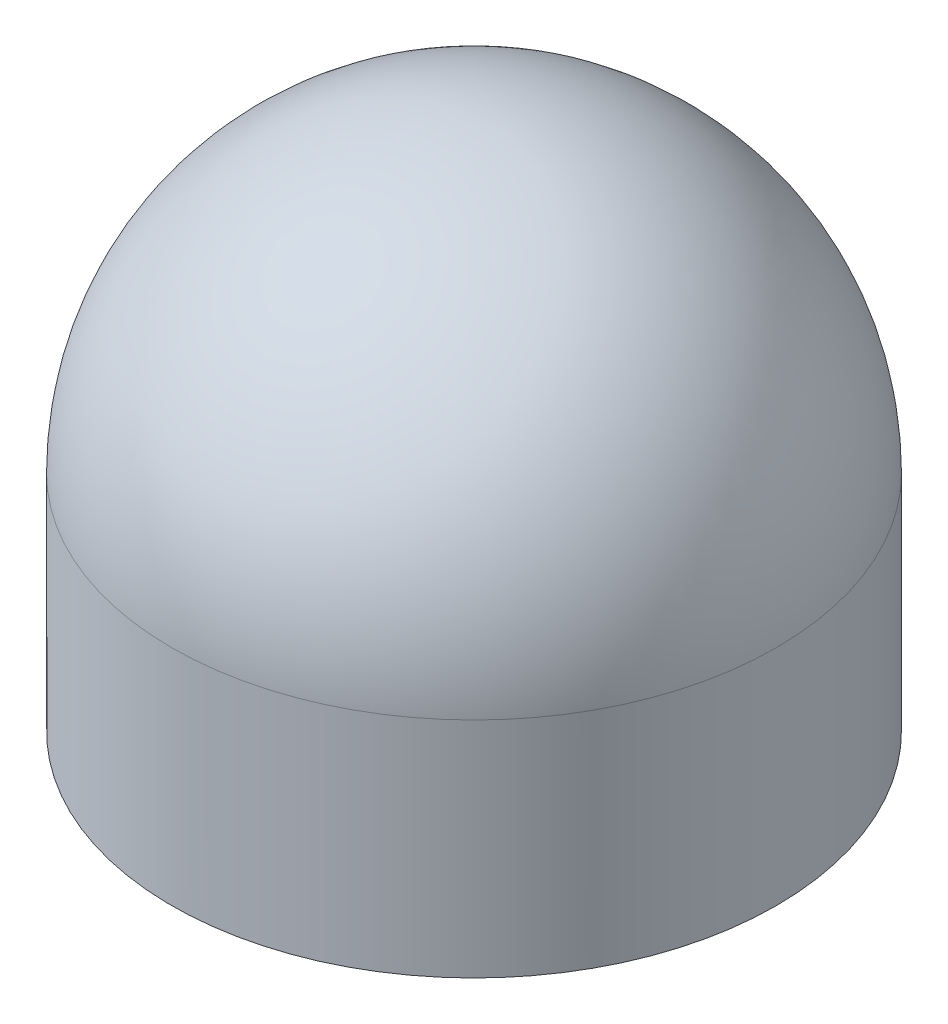
SolidWorks part; units mm, degrees
ref_plane "Płaszczyzna przednia" through (0, 0, 0) normal (0, 0, 1) x (1, 0, 0)
ref_plane "Płaszczyzna górna" through (0, 0, 0) normal (0, 1, 0) x (1, 0, 0)
ref_plane "Płaszczyzna prawa" through (0, 0, 0) normal (1, 0, 0) x (0, 0, -1)
sketch "Szkic1" plane through (0, 0, 0) normal (0, 0, 1) x (1, 0, 0)
  line L0 (0, 0) -> (0, 20) construction
  line L1 (-11.5, 0) -> (-11.5, 8.5)
  line L2 (-10, 0) -> (-10, 8.5)
  line L3 (-10, 0) -> (-11.5, 0)
  line L4 (0, 20) -> (0, 18.5)
  arc A0 (-11.5, 8.5) -> (0, 20) centre (0, 8.5) cw
  arc A1 (-10, 8.5) -> (0, 18.5) centre (0, 8.5) cw
  dimension "D2" = 20
  dimension "D3" = 20
  dimension "D1" = 1.5
revolve "Obrót1" add sketch "Szkic1" angle 360 about L0
